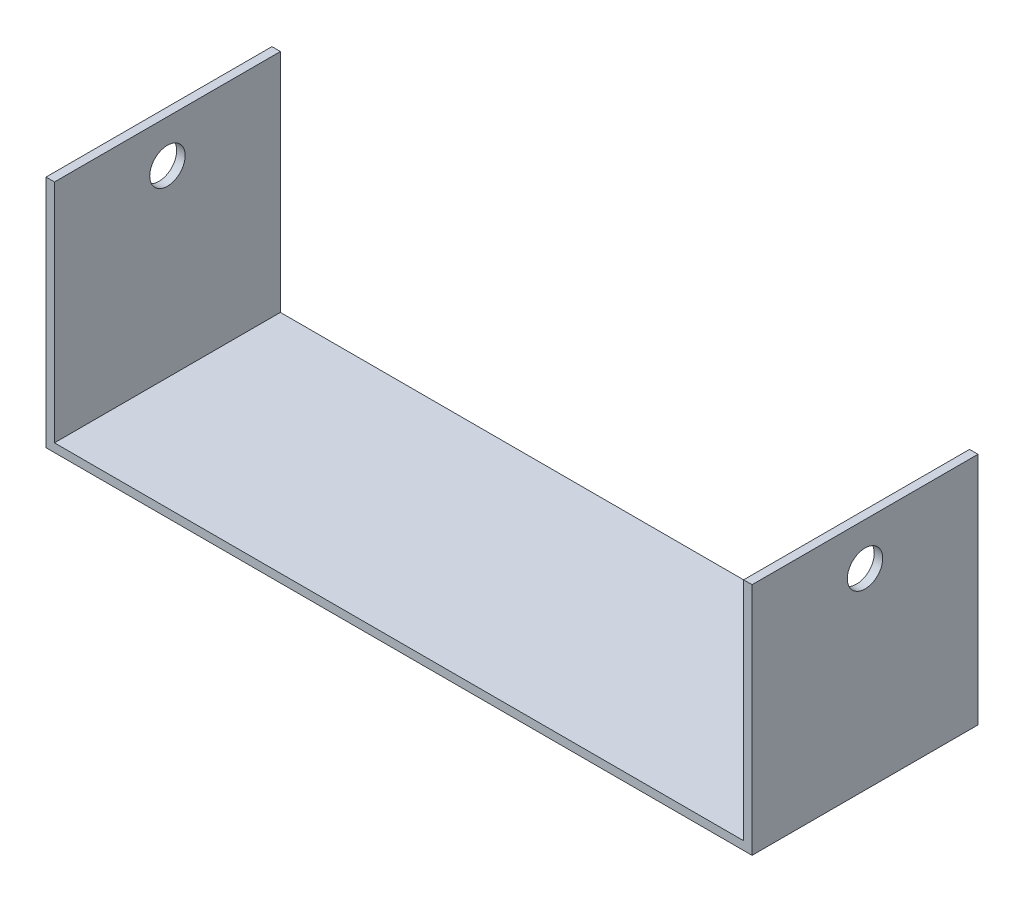
SolidWorks part; units mm, degrees
ref_plane "Front Plane" through (0, 0, 0) normal (0, 0, 1) x (1, 0, 0)
ref_plane "Top Plane" through (0, 0, 0) normal (0, 1, 0) x (1, 0, 0)
ref_plane "Right Plane" through (0, 0, 0) normal (1, 0, 0) x (0, 0, -1)
sketch "Sketch1" plane through (0, 0, 0) normal (0, 0, 1) x (1, 0, 0)
  line L0 (0, 72.5294) -> (0, 0) construction
  line L1 (125, 0) -> (-125, 0)
  line L2 (-125, 0) -> (-125, 83)
  line L3 (-125, 83) -> (-122, 83)
  line L4 (-122, 83) -> (-122, 3)
  line L5 (-122, 3) -> (122, 3)
  line L6 (122, 83) -> (122, 3)
  line L7 (125, 83) -> (122, 83)
  line L8 (125, 0) -> (125, 83)
  point P9 (0, 3)
  dimension "D1" = 3
  dimension "D2" = 3
  dimension "D3" = 244
  dimension "D4" = 80
extrude "Boss-Extrude1" add sketch "Sketch1" along normal blind 80
sketch "Sketch2" plane through (-125, 0, 0) normal (-1, 0, 0) x (0, 0, 1)
  circle A0 centre (40, 67.9712) radius 6.2728
extrude "Cut-Extrude1" cut sketch "Sketch2" against normal blind 500
